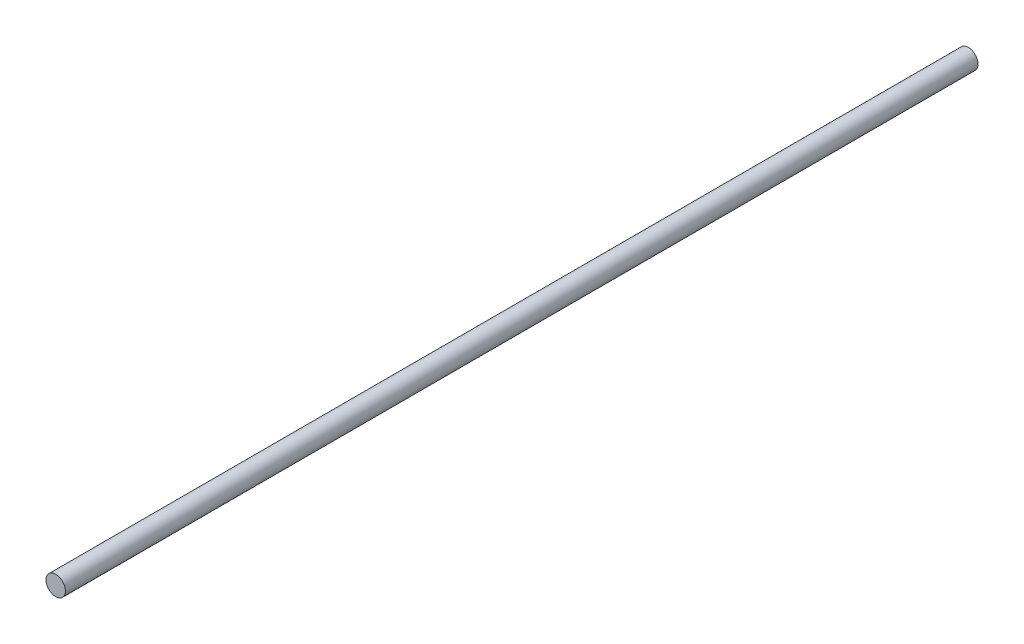
SolidWorks part; units mm, degrees
ref_plane "前视基准面" through (0, 0, 0) normal (0, 0, 1) x (1, 0, 0)
ref_plane "上视基准面" through (0, 0, 0) normal (0, 1, 0) x (1, 0, 0)
ref_plane "右视基准面" through (0, 0, 0) normal (1, 0, 0) x (0, 0, -1)
sketch "草图1" plane through (0, 0, 0) normal (0, 0, 1) x (1, 0, 0)
  circle A0 centre (0, 0) radius 10
  dimension "D1" = 20
extrude "凸台-拉伸1" add sketch "草图1" along normal blind 940
